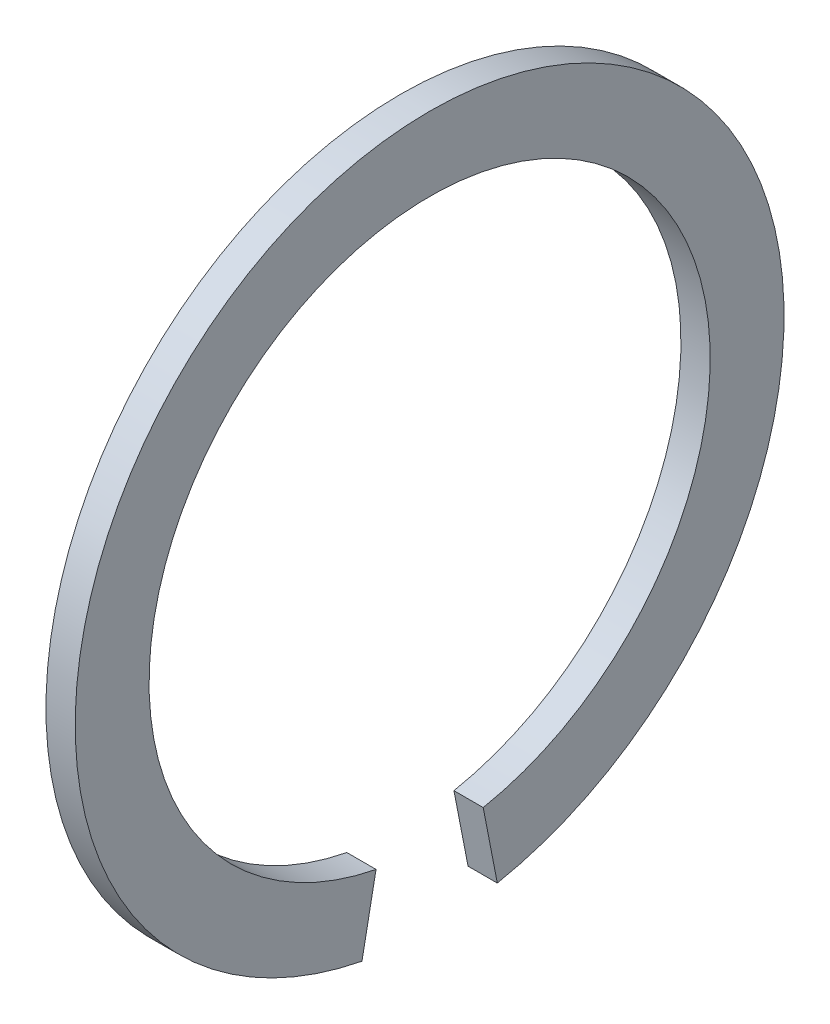
SolidWorks part; units mm, degrees
ref_plane "Front Plane" through (0, 0, 0) normal (0, 0, 1) x (1, 0, 0)
ref_plane "Top Plane" through (0, 0, 0) normal (0, 1, 0) x (1, 0, 0)
ref_plane "Right Plane" through (0, 0, 0) normal (1, 0, 0) x (0, 0, -1)
sketch "Sketch1" plane through (0, 0, 0) normal (1, 0, 0) x (0, 0, -1)
  line L0 (-1.9954, -10.2577) -> (-2.5205, -12.9571)
  line L2 (1.9954, -10.2577) -> (2.5205, -12.9571)
  arc A0 (1.9954, -10.2577) -> (-1.9954, -10.2577) centre (0, 0) ccw
  arc A1 (2.5205, -12.9571) -> (-2.5205, -12.9571) centre (0, 0) ccw
  dimension "D1" = 20.9
  dimension "D2" = 26.4
extrude "Boss-Extrude1" add sketch "Sketch1" along normal blind 1.09
